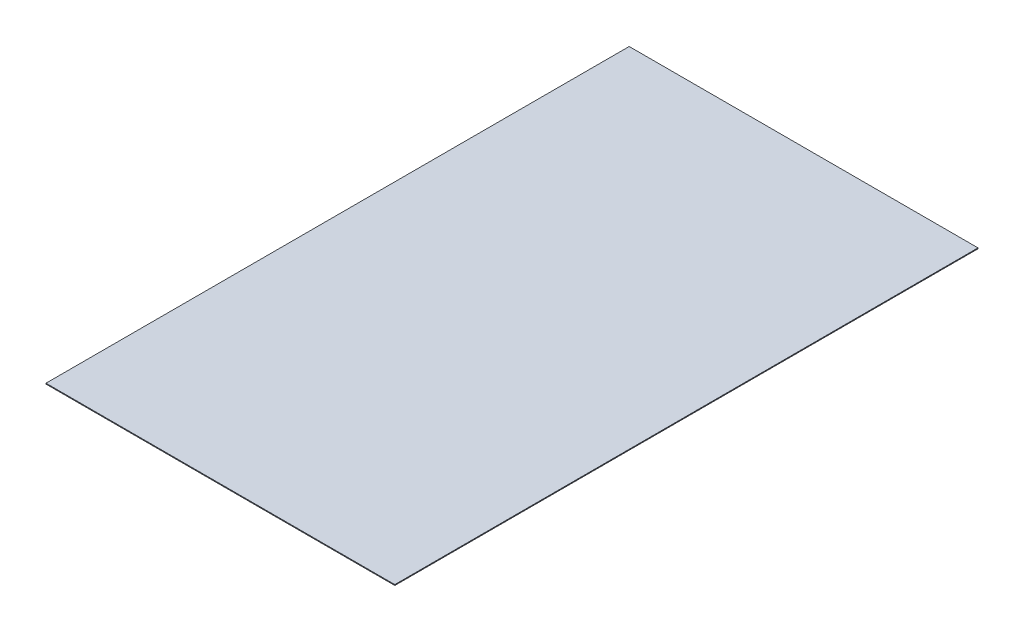
SolidWorks part; units mm, degrees
material "Литая легированная сталь"
ref_plane "Спереди" through (0, 0, 0) normal (0, 0, 1) x (1, 0, 0)
ref_plane "Сверху" through (0, 0, 0) normal (0, 1, 0) x (1, 0, 0)
ref_plane "Справа" through (0, 0, 0) normal (1, 0, 0) x (0, 0, -1)
sketch "Эскиз2" plane through (0, 0, 0) normal (0, 1, 0) x (1, 0, 0)
  line L1 (0, 0) -> (1274, 0)
  line L2 (0, 0) -> (0, 2130)
  line L3 (0, 2130) -> (1274, 2130)
  line L4 (1274, 0) -> (1274, 2130)
extrude "Бобышка-Вытянуть1" add sketch "Эскиз2" along normal blind 3
